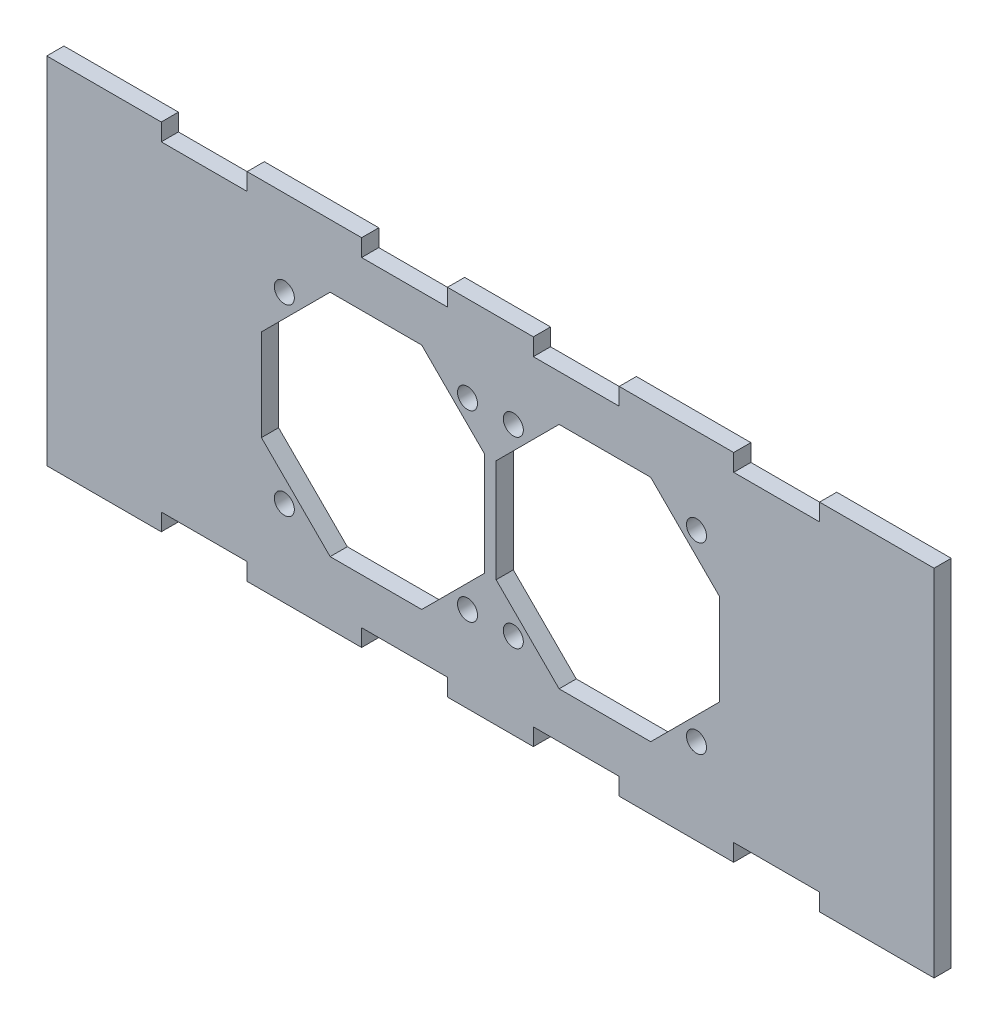
SolidWorks part; units mm, degrees
ref_plane "Přední rovina" through (0, 0, 0) normal (0, 0, 1) x (1, 0, 0)
ref_plane "Horní rovina" through (0, 0, 0) normal (0, 1, 0) x (1, 0, 0)
ref_plane "Pravá rovina" through (0, 0, 0) normal (1, 0, 0) x (0, 0, -1)
sketch "Skica1" plane through (0, 0, 0) normal (0, 0, 1) x (1, 0, 0)
  line L0 (20, 3) -> (35, 3)
  line L1 (0, 0) -> (20, 0)
  line L2 (0, 0) -> (0, 62)
  line L4 (77.5, 0) -> (77.5, 11)
  line L5 (20, 3) -> (20, 0)
  line L6 (35, 3) -> (35, 0)
  line L7 (55, 3) -> (55, 0)
  line L8 (70, 3) -> (70, 0)
  line L9 (35, 0) -> (55, 0)
  line L10 (70, 0) -> (77.5, 0)
  line L11 (55, 3) -> (70, 3)
  line L12 (77.5, 31) -> (-67.3238, 31) construction
  line L13 (20, 59) -> (20, 62)
  line L14 (0, 62) -> (20, 62)
  line L15 (70, 62) -> (77.5, 62)
  line L16 (70, 59) -> (70, 62)
  line L17 (55, 59) -> (70, 59)
  line L18 (55, 59) -> (55, 62)
  line L19 (35, 62) -> (55, 62)
  line L20 (35, 59) -> (35, 62)
  line L21 (20, 59) -> (35, 59)
  line L22 (65.5, 51) -> (49.5, 51)
  line L23 (37.5, 39) -> (37.5, 23)
  line L25 (65.5, 11) -> (49.5, 11)
  line L27 (77.5, 51) -> (77.5, 62)
  line L28 (49.5, 51) -> (37.5, 39)
  line L29 (49.5, 11) -> (37.5, 23)
  line L30 (65.5, 51) -> (76.5, 40)
  line L33 (77.5, 51) -> (77.5, 41.6537)
  line L34 (77.5, 20.3463) -> (77.5, 41.6537)
  line L35 (76.5, 40) -> (76.5, 22)
  line L36 (77.5, 11) -> (77.5, 20.3463)
  line L37 (65.5, 11) -> (76.5, 22)
  line L38 (57.5, 51) -> (57.5, 11) construction
  circle A0 centre (41.5, 47) radius 1.75
  circle A1 centre (41.5, 15) radius 1.75
  circle A2 centre (73.5, 15) radius 1.75
  circle A3 centre (73.5, 47) radius 1.75
  point P24 (37.5, 51)
  point P27 (37.5, 11)
  point P28 (35.5, 31)
  point P40 (76.5, 31)
  dimension "D19" = 3.5
  dimension "D1" = 20
  dimension "D2" = 15
  dimension "D3" = 20
  dimension "D4" = 3
  dimension "D5" = 15
  dimension "D6" = 62
  dimension "D7" = 77.5
  dimension "D8" = 40
  dimension "D9" = 40
  dimension "D10" = 12
  dimension "D11" = 1
  dimension "D14" = 45
  dimension "D15" = 18
  dimension "D16" = 4
  dimension "D17" = 20
  dimension "D18" = 4
  dimension "D20" = 20
extrude "Přidat vysunutím1" add sketch "Skica1" along normal blind 3
mirror "Zrcadlit1" about plane through (77.5, 51, 3) normal (-1, 0, 0) of "Přidat vysunutím1"
